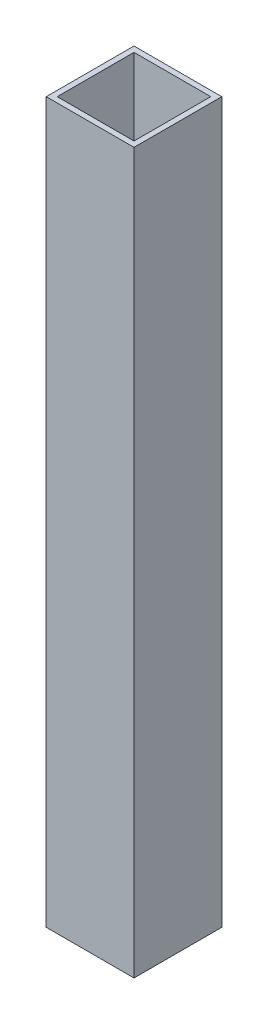
SolidWorks part; units mm, degrees
ref_plane "Front Plane" through (0, 0, 0) normal (0, 0, 1) x (1, 0, 0)
ref_plane "Top Plane" through (0, 0, 0) normal (0, 1, 0) x (1, 0, 0)
ref_plane "Right Plane" through (0, 0, 0) normal (1, 0, 0) x (0, 0, -1)
sketch "Sketch3" plane through (0, 0, 0) normal (0, 1, 0) x (1, 0, 0)
  line L1 (-25.4, -25.4) -> (25.4, -25.4)
  line L2 (-25.4, -25.4) -> (-25.4, 25.4)
  line L3 (-25.4, 25.4) -> (25.4, 25.4)
  line L4 (25.4, -25.4) -> (25.4, 25.4)
  line L5 (-25.4, -25.4) -> (25.4, 25.4) construction
  line L6 (-25.4, 25.4) -> (25.4, -25.4) construction
  line L7 (-22.225, -22.225) -> (22.225, -22.225)
  line L8 (-22.225, -22.225) -> (-22.225, 22.225)
  line L9 (-22.225, 22.225) -> (22.225, 22.225)
  line L10 (22.225, -22.225) -> (22.225, 22.225)
  line L11 (-22.225, -22.225) -> (22.225, 22.225) construction
  line L12 (-22.225, 22.225) -> (22.225, -22.225) construction
  point P0 (0, 0)
  point P6 (0, 0)
  dimension "D1" = 50.8
  dimension "D2" = 50.8
  dimension "D3" = 3.175
extrude "Boss-Extrude3" add sketch "Sketch3" along normal blind 416.4076
ref_plane "Plane1" through (-25.4, 416.4076, 25.4) normal (1, 0, 0) x (0, 0, -1)
